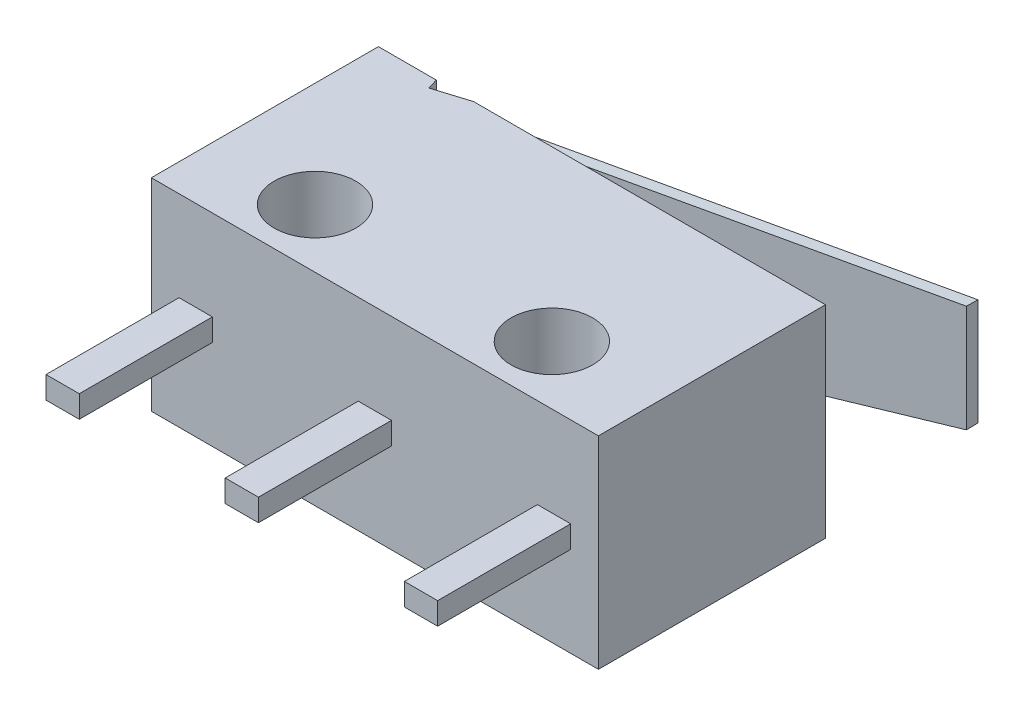
SolidWorks part; units mm, degrees
ref_plane "Front Plane" through (0, 0, 0) normal (0, 0, 1) x (1, 0, 0)
ref_plane "Top Plane" through (0, 0, 0) normal (0, 1, 0) x (1, 0, 0)
ref_plane "Right Plane" through (0, 0, 0) normal (1, 0, 0) x (0, 0, -1)
sketch "Sketch1" plane through (0, 0, 0) normal (0, 1, 0) x (1, 0, 0)
  line L0 (0, 3.2512) -> (0, -3.2512) construction
  line L1 (-6.4008, 3.2512) -> (6.4008, 3.2512)
  line L2 (-6.4008, 3.2512) -> (-6.4008, -3.2512)
  line L3 (-6.4008, -3.2512) -> (6.4008, -3.2512)
  line L4 (6.4008, 3.2512) -> (6.4008, -3.2512)
  line L5 (-6.4008, 3.2512) -> (6.4008, -3.2512) construction
  line L6 (-6.4008, -3.2512) -> (6.4008, 3.2512) construction
  circle A0 centre (3.3909, -1.5748) radius 1.1684
  circle A1 centre (-3.3909, -1.5748) radius 1.1684
  point P0 (0, 0)
  dimension "D3" = 2.3368
  dimension "D4" = 1.6764
  dimension "D5" = 3.3909
  dimension "D1" = 12.8016
  dimension "D2" = 6.5024
extrude "Boss-Extrude1" add sketch "Sketch1" along normal blind 5.7912
sketch "Sketch2" plane through (0, 0, -3.2512) normal (0, 0, -1) x (-1, 0, 0)
  line L0 (6.4008, 2.8956) -> (-6.4008, 2.8956) construction
  line L1 (6.4008, 5.7912) -> (6.4008, 0) construction
  line L2 (-6.4008, 5.7912) -> (-6.4008, 0) construction
  line L4 (1.4478, 4.6736) -> (2.4638, 4.6736)
  line L5 (1.4478, 4.6736) -> (1.4478, 1.1176)
  line L6 (1.4478, 1.1176) -> (2.4638, 1.1176)
  line L7 (2.4638, 4.6736) -> (2.4638, 1.1176)
  line L8 (1.4478, 4.6736) -> (2.4638, 1.1176) construction
  line L9 (1.4478, 1.1176) -> (2.4638, 4.6736) construction
  point P6 (1.9558, 2.8956)
  dimension "D1" = 4.445
  dimension "D2" = 1.016
  dimension "D3" = 3.556
extrude "Boss-Extrude2" add sketch "Sketch2" along normal blind 1.27
sketch "Sketch3" plane through (0, 1.1176, 0) normal (0, -1, 0) x (1, 0, 0)
  line L0 (-1.4478, -3.2512) -> (-1.4478, -4.5212)
  line L1 (-1.4478, -4.5212) -> (-2.4638, -4.5212)
  line L2 (-2.4638, -4.5212) -> (-2.4638, -3.2512)
  arc A0 (-2.4638, -3.2512) -> (-1.4478, -3.2512) centre (-1.9558, -3.2512) ccw
extrude "Cut-Extrude1" cut sketch "Sketch3" against normal blind 4.318
sketch "Sketch4" plane through (0, 5.7912, 0) normal (0, 1, 0) x (1, 0, 0)
  line L0 (-3.6734, 3.2512) -> (-4.7441, 3.2512)
  line L2 (-4.7441, 3.2512) -> (7.0923, 6.9265)
  line L3 (7.0923, 6.9265) -> (7.0923, 6.594)
  line L4 (7.0923, 6.594) -> (-3.6734, 3.2512)
  line L5 (6.4008, 3.2512) -> (-6.4008, 3.2512) construction
  line L8 (-2.4638, 3.2512) -> (-1.4478, 3.2512)
  line L9 (-2.4638, 3.2512) -> (-1.4478, 3.2512) construction
  arc A1 (-1.4478, 3.2512) -> (-2.4638, 3.2512) centre (-1.9558, 3.2512) ccw
  arc A2 (-1.4478, 3.2512) -> (-2.4638, 3.2512) centre (-1.9558, 3.2512) ccw construction
  dimension "D2" = 0.3175
  dimension "D3" = 17.25
  dimension "D4" = 11.8364
  dimension "D1" = 0
extrude "Boss-Extrude6" add sketch "Sketch4" against normal up to surface (5.7912 mm away) up to face at (3.3909, 0, 2.7432)
sketch "Sketch6" plane through (-1.3379, 0, -4.3088) normal (-0.2965, 0, -0.955) x (-0.955, 0, 0.2965)
  line L0 (3.5666, 0.5129) -> (-8.8273, 1.3685)
  line L1 (3.5666, 0) -> (3.5666, 5.7912) construction
  line L2 (-8.8273, 0) -> (-8.8273, 5.7912) construction
  line L3 (-8.8273, 2.8956) -> (3.5666, 2.8956) construction
  line L4 (3.5666, 1.6894) -> (-0.8915, 2.1634)
  line L5 (3.5666, 1.6894) -> (3.5666, 4.1018)
  line L6 (3.5666, 0.5129) -> (3.5666, 0)
  line L7 (3.5666, 0) -> (-8.8273, 0)
  line L8 (-8.8273, 0) -> (-8.8273, 1.3685)
  line L9 (3.5666, 4.1018) -> (-0.8915, 3.6278)
  line L10 (3.5666, 5.2783) -> (3.5666, 5.7912)
  line L11 (3.5666, 5.7912) -> (-8.8273, 5.7912)
  line L12 (-8.8273, 5.7912) -> (-8.8273, 4.4227)
  line L13 (3.5666, 5.2783) -> (-8.8273, 4.4227)
  arc A0 (-0.8915, 2.1634) -> (-0.8915, 3.6278) centre (-0.8137, 2.8956) cw
extrude "Cut-Extrude2" cut sketch "Sketch6" against normal up to surface (0.3175 mm away) up to face at (1.7094, 2.8956, -4.9226)
sketch "Sketch7" plane through (0, 0, 3.2512) normal (0, 0, 1) x (1, 0, 0)
  line L0 (-6.4008, 2.8956) -> (6.4008, 2.8956) construction
  line L1 (-6.4008, 5.7912) -> (-6.4008, 0) construction
  line L2 (6.4008, 5.7912) -> (6.4008, 0) construction
  line L3 (-5.6071, 3.2131) -> (-4.6546, 3.2131)
  line L4 (-0.4763, 3.2131) -> (0.4762, 3.2131)
  line L5 (-0.4763, 3.2131) -> (-0.4763, 2.5781)
  line L6 (-0.4763, 2.5781) -> (0.4762, 2.5781)
  line L7 (0.4762, 3.2131) -> (0.4762, 2.5781)
  line L8 (-0.4763, 3.2131) -> (0.4762, 2.5781) construction
  line L9 (-0.4763, 2.5781) -> (0.4762, 3.2131) construction
  line L10 (-5.6071, 3.2131) -> (-5.6071, 2.5781)
  line L11 (-5.6071, 2.5781) -> (-4.6546, 2.5781)
  line L12 (-4.6546, 3.2131) -> (-4.6546, 2.5781)
  line L13 (-5.6071, 3.2131) -> (-4.6546, 2.5781) construction
  line L14 (-5.6071, 2.5781) -> (-4.6546, 3.2131) construction
  line L15 (0, 5.7912) -> (0, 0) construction
  line L16 (-6.4008, 5.7912) -> (6.4008, 5.7912) construction
  line L17 (5.6071, 2.5781) -> (4.6545, 3.2131) construction
  line L18 (5.607, 3.2131) -> (4.6546, 2.5781) construction
  line L19 (4.6545, 3.2131) -> (4.6546, 2.5781)
  line L20 (5.6071, 2.5781) -> (4.6546, 2.5781)
  line L21 (5.607, 3.2131) -> (5.6071, 2.5781)
  line L22 (5.607, 3.2131) -> (4.6545, 3.2131)
  point P6 (0, 2.8956)
  point P11 (-5.1308, 2.8956)
  point P25 (5.1308, 2.8956)
  dimension "D1" = 0.635
  dimension "D2" = 0.9525
  dimension "D3" = 1.27
extrude "Boss-Extrude7" add sketch "Sketch7" along normal blind 3.81
